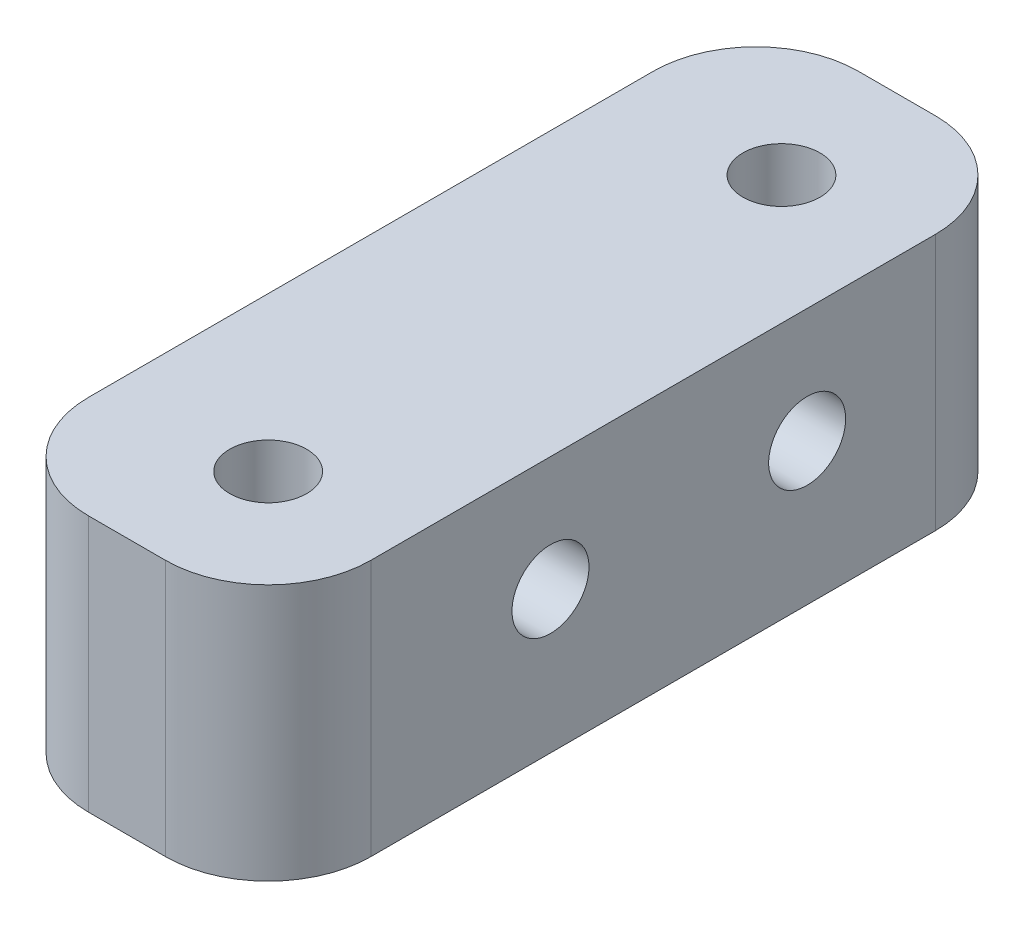
SolidWorks part; units mm, degrees
ref_plane "Front Plane" through (0, 0, 0) normal (0, 0, 1) x (1, 0, 0)
ref_plane "Top Plane" through (0, 0, 0) normal (0, 1, 0) x (1, 0, 0)
ref_plane "Right Plane" through (0, 0, 0) normal (1, 0, 0) x (0, 0, -1)
sketch "Sketch1" plane through (0, 0, 0) normal (0, 1, 0) x (1, 0, 0)
  line L1 (0, 0) -> (11, 0)
  line L2 (0, 0) -> (0, 30)
  line L3 (0, 30) -> (11, 30)
  line L4 (11, 0) -> (11, 30)
  circle A0 centre (6, 25) radius 1.5
  circle A1 centre (6, 5) radius 1.5
  dimension "D3" = 5
  dimension "D4" = 5
  dimension "D5" = 5
  dimension "D6" = 5
  dimension "D7" = 3
  dimension "D1" = 11
  dimension "D2" = 30
extrude "Boss-Extrude1" add sketch "Sketch1" along normal blind 10
sketch "Sketch2" plane through (11, 0, 0) normal (1, 0, 0) x (0, 0, -1)
  line L0 (0, 10) -> (0, 0) construction
  circle A0 centre (11, 5.5305) radius 1.5
  circle A1 centre (21, 5.5305) radius 1.5
  dimension "D1" = 3
  dimension "D2" = 10
  dimension "D3" = 11
extrude "Cut-Extrude1" cut sketch "Sketch2" against normal through all
fillet "Fillet1" radius 4 4 edges at (0, 5, -30) (11, 5, -30) (0, 5, 0) (11, 5, 0)
